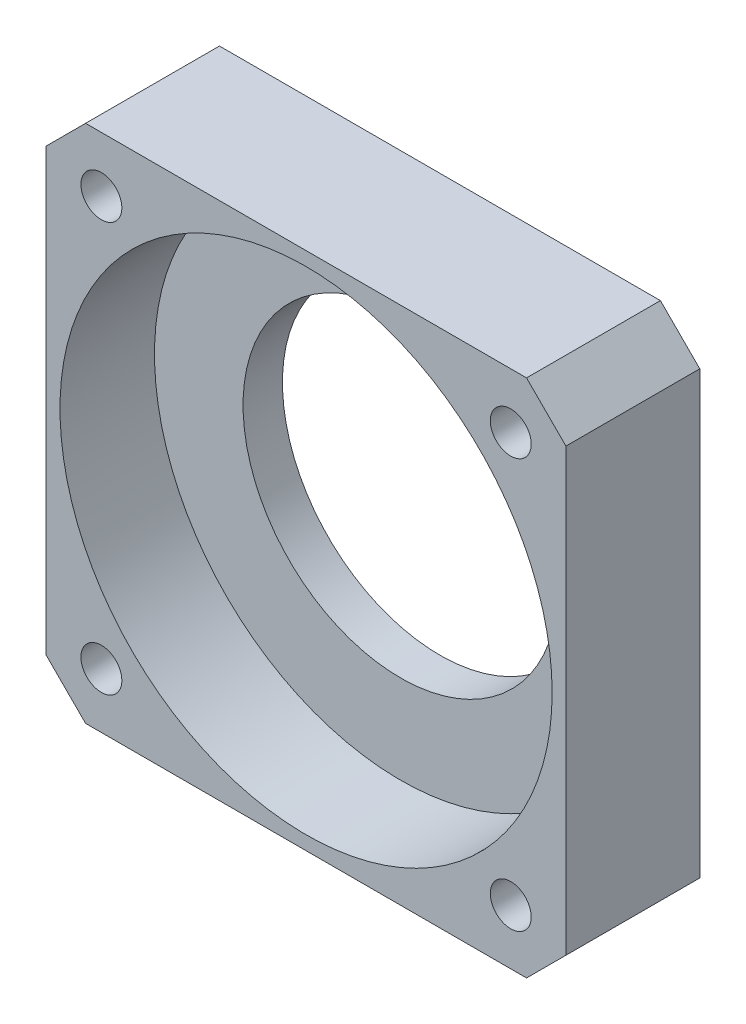
SolidWorks part; units mm, degrees
material "2024-T3"
ref_plane "Front Plane" through (0, 0, 0) normal (0, 0, 1) x (1, 0, 0)
ref_plane "Top Plane" through (0, 0, 0) normal (0, 1, 0) x (1, 0, 0)
ref_plane "Right Plane" through (0, 0, 0) normal (1, 0, 0) x (0, 0, -1)
sketch "Sketch1" plane through (0, 0, 0) normal (0, 0, 1) x (1, 0, 0)
  line L0 (0, 0) -> (41.91, 41.91) construction
  line L1 (0, 0) -> (41.91, 0)
  line L2 (0, 0) -> (0, 41.91)
  line L3 (0, 41.91) -> (41.91, 41.91)
  line L4 (41.91, 0) -> (41.91, 41.91)
  line L5 (4.4493, 37.4607) -> (20.955, 20.955) construction
  circle A0 centre (37.4607, 37.4607) radius 1.6497
  circle A1 centre (37.4607, 4.4493) radius 1.6497
  circle A2 centre (4.4493, 4.4493) radius 1.6497
  circle A3 centre (4.4493, 37.4607) radius 1.6497
  circle A4 centre (20.955, 20.955) radius 12.7
  point P7 (20.955, 20.955)
  point P17 (20.955, 20.955)
  dimension "D3" = 3.2995
  dimension "D7" = 25.4
  dimension "D1" = 41.91
  dimension "D2" = 41.91
  dimension "D4" = 23.3426
  dimension "D6" = 23.3426
  dimension "D5" = 4
extrude "Boss-Extrude1" add sketch "Sketch1" along normal blind 10.795
sketch "Sketch3" plane through (0, 0, 10.795) normal (0, 0, 1) x (1, 0, 0)
  circle A0 centre (20.955, 20.955) radius 19.8438
  dimension "D1" = 39.6875
extrude "Cut-Extrude2" cut sketch "Sketch3" against normal blind 7.62
chamfer "Chamfer1" distance 3.175 angle 45 4 edges at (0, 0, 5.3975) (41.91, 0, 5.3975) (41.91, 41.91, 5.3975) (0, 41.91, 5.3975)
